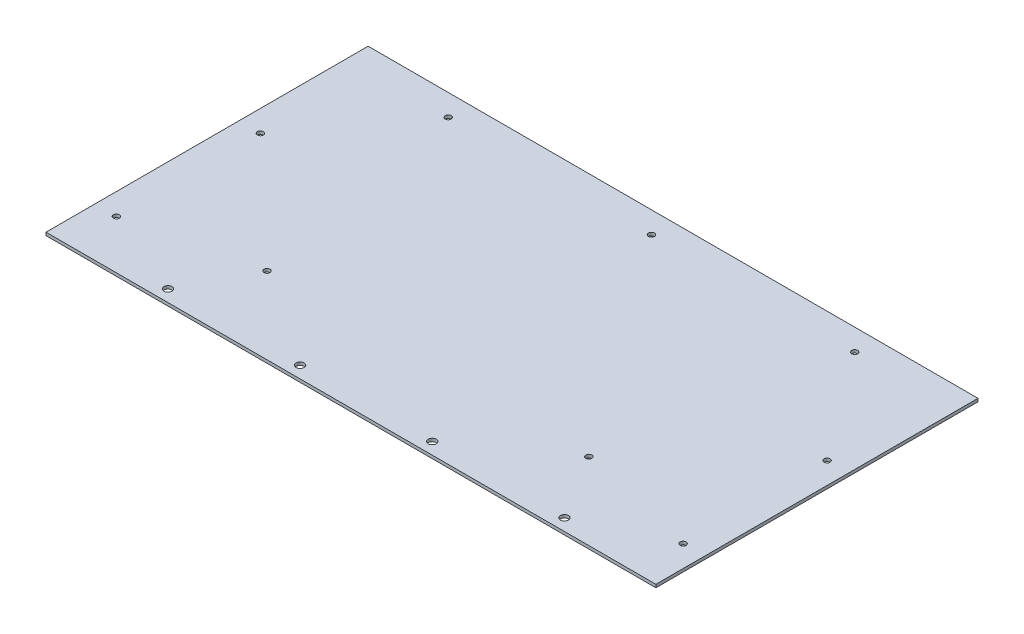
SolidWorks part; units mm, degrees
material "6061-T6 (SS)"
ref_plane "X-Y Datum" through (0, 0, 0) normal (0, 0, 1) x (1, 0, 0)
ref_plane "X-Z Datum" through (0, 0, 0) normal (0, 1, 0) x (1, 0, 0)
ref_plane "Y-Z Datum" through (0, 0, 0) normal (1, 0, 0) x (0, 0, -1)
sketch "Sketch1" plane through (0, 0, 0) normal (0, 0, 1) x (1, 0, 0)
  line L1 (-228.6, -1.143) -> (228.6, -1.143)
  line L2 (-228.6, -1.143) -> (-228.6, 1.143)
  line L3 (-228.6, 1.143) -> (228.6, 1.143)
  line L4 (228.6, -1.143) -> (228.6, 1.143)
  line L5 (-228.6, -1.143) -> (228.6, 1.143) construction
  line L6 (-228.6, 1.143) -> (228.6, -1.143) construction
  point P0 (0, 0)
  dimension "D1" = 2.286
  dimension "D2" = 457.2
extrude "Boss-Extrude1" add sketch "Sketch1" along normal blind 238.3152
sketch "Sketch2" plane through (0, 0, 0) normal (0, 0, -1) x (-1, 0, 0)
  line L22 (-228.6, 1.143) -> (-228.6, -1.143)
  line L23 (-228.6, -1.143) -> (228.6, -1.143)
  line L24 (228.6, -1.143) -> (228.6, 1.143)
  line L25 (228.6, 1.143) -> (-228.6, 1.143)
  line L26 (-228.6, 1.143) -> (-228.6, -1.143)
  line L27 (-228.6, -1.143) -> (228.6, -1.143)
  line L28 (228.6, -1.143) -> (228.6, 1.143)
  line L29 (228.6, 1.143) -> (-228.6, 1.143)
  dimension "D1" = 0
extrude "Boss-Extrude2" add sketch "Sketch2" along normal blind 3.175
sketch "Sketch9" plane through (0, 1.143, 0) normal (0, 1, 0) x (1, 0, 0)
  line L0 (-146.05, -238.3152) -> (-146.05, -229.4252) construction
  line L1 (228.6, -238.3152) -> (-228.6, -238.3152) construction
  line L2 (-228.6, -238.3152) -> (-228.6, 3.175) construction
  circle A0 centre (-146.05, -229.4252) radius 3
  dimension "D2" = 82.55
  dimension "D3" = 6
  dimension "D1" = 8.89
extrude "Cut-Extrude10" cut sketch "Sketch9" against normal blind 2.54
pattern_linear "LPattern1" count 4 spacing 99.06 along (1, 0, 0) of "Cut-Extrude10"
sketch "Sketch10" plane through (0, -1.143, 0) normal (0, -1, 0) x (1, 0, 0)
  circle A0 centre (151.13, 229.4252) radius 3 construction
  circle A1 centre (52.07, 229.4252) radius 3 construction
  circle A2 centre (-46.99, 229.4252) radius 3 construction
  circle A3 centre (-146.05, 229.4252) radius 3 construction
  circle A4 centre (151.13, 229.4252) radius 3
  circle A5 centre (52.07, 229.4252) radius 3
  circle A6 centre (-46.99, 229.4252) radius 3
  circle A7 centre (-146.05, 229.4252) radius 3
sketch "Sketch12" plane through (0, -1.143, 0) normal (0, -1, 0) x (1, 0, 0)
  point P0 (-212.419, 93.7748)
  point P1 (-152.4, 13.0175)
  point P3 (0, 13.0175)
  point P5 (152.4, 13.0175)
  point P7 (212.419, 93.7748)
  point P9 (212.419, 201.7248)
  point P11 (120.65, 180.586)
  point P15 (-120.65, 180.586)
  point P17 (-212.419, 201.7248)
hole_wizard "M4 Clearance Hole1" positions "Sketch12" profile "Sketch13" hole size "M4" standard "ANSI Metric" end condition through all
sketch "Sketch13" plane through (-212.419, -1.143, 93.7748) normal (1, 0, 0) x (0, 0, -1)
  line L0 (0, 0) -> (0, 2.286)
  line L1 (0, 2.286) -> (2.25, 2.286)
  line L2 (2.25, 2.286) -> (2.25, 0)
  line L5 (2.25, 0) -> (0, 0)
  line L11 (0, -6.35) -> (0, 107.95) construction
  dimension "Thru Hole Dia." = 4.5
  dimension "Thru Hole Depth" = 2.286
